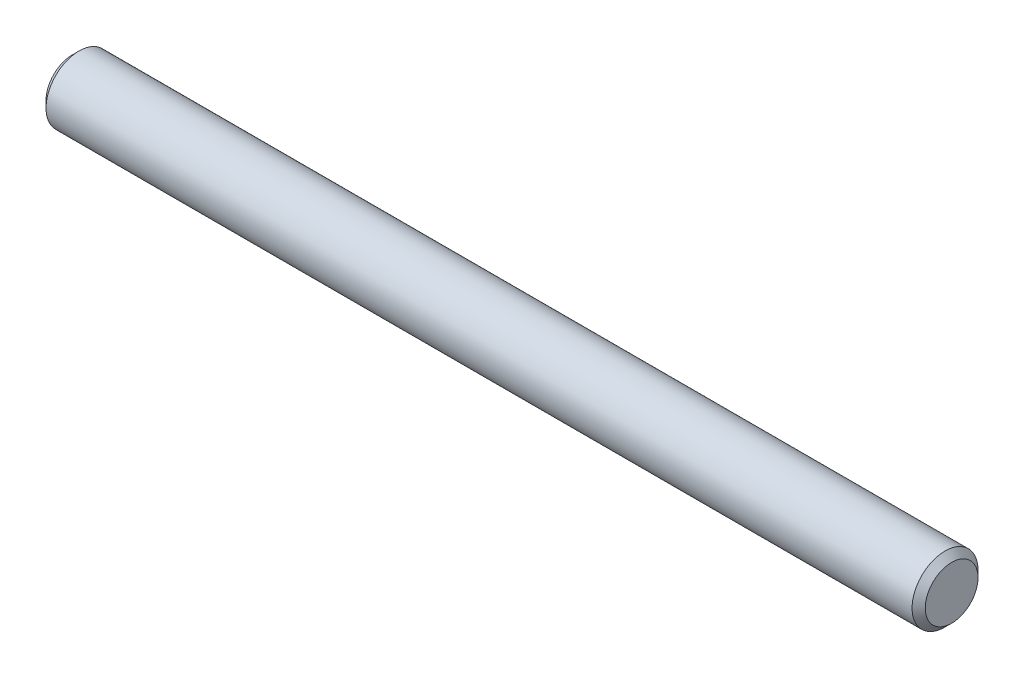
SolidWorks part; units mm, degrees
ref_plane "Front" through (0, 0, 0) normal (0, 0, 1) x (1, 0, 0)
ref_plane "Top" through (0, 0, 0) normal (0, 1, 0) x (1, 0, 0)
ref_plane "Right" through (0, 0, 0) normal (1, 0, 0) x (0, 0, -1)
sketch "Sketch1" plane through (0, 0, 0) normal (0, 0, 1) x (1, 0, 0)
  line L0 (-63.5, 0) -> (63.5, 0) construction
  line L1 (63.5, 4.7625) -> (63.5, -4.7625) construction
  line L2 (-63.5, 4.7625) -> (-63.5, -4.7625) construction
  dimension "Length" = 127
  dimension "Diameter" = 9.525
sketch "Sketch2" plane through (0, 0, 0) normal (1, 0, 0) x (0, 0, -1)
  circle A0 centre (0, 0) radius 4.7625
extrude "Extrude1" add sketch "Sketch2" against normal up to vertex (63.5 mm away) and the other way up to vertex (63.5 mm away) up to point (-63.5, 4.7625, 0) other way up to point (63.5, 4.7625, 0)
chamfer "Chamfer1" distance 0.9525 angle 45 2 edges at (63.5, 0, -4.7625) (-63.5, 0, -4.7625)
equation "\"D1@Chamfer1\" = \"Diameter@Sketch1\"*.1"
